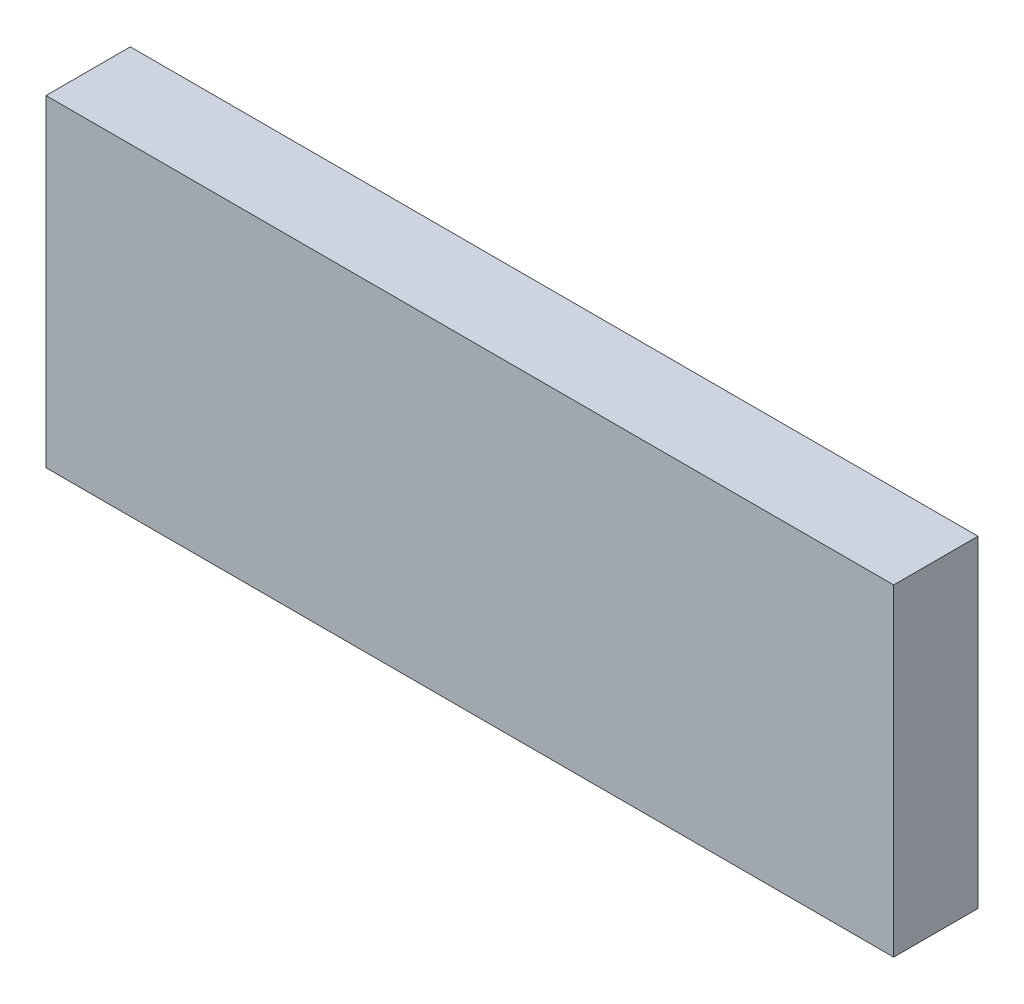
SolidWorks part; units mm, degrees
material "Esc skywalker v2"
ref_plane "Plano frontal" through (0, 0, 0) normal (0, 0, 1) x (1, 0, 0)
ref_plane "Plano superior" through (0, 0, 0) normal (0, 1, 0) x (1, 0, 0)
ref_plane "Plano direito" through (0, 0, 0) normal (1, 0, 0) x (0, 0, -1)
sketch "Esboço1" plane through (0, 0, 0) normal (0, 0, 1) x (1, 0, 0)
  line L1 (-48.25, -18.35) -> (48.25, -18.35)
  line L2 (-48.25, -18.35) -> (-48.25, 18.35)
  line L3 (-48.25, 18.35) -> (48.25, 18.35)
  line L4 (48.25, -18.35) -> (48.25, 18.35)
  line L5 (-48.25, -18.35) -> (48.25, 18.35) construction
  line L6 (-48.25, 18.35) -> (48.25, -18.35) construction
  point P0 (0, 0)
  dimension "D1" = 96.5
  dimension "D2" = 36.7
extrude "Ressalto-extrusão1" add sketch "Esboço1" along normal mid plane 9.6
